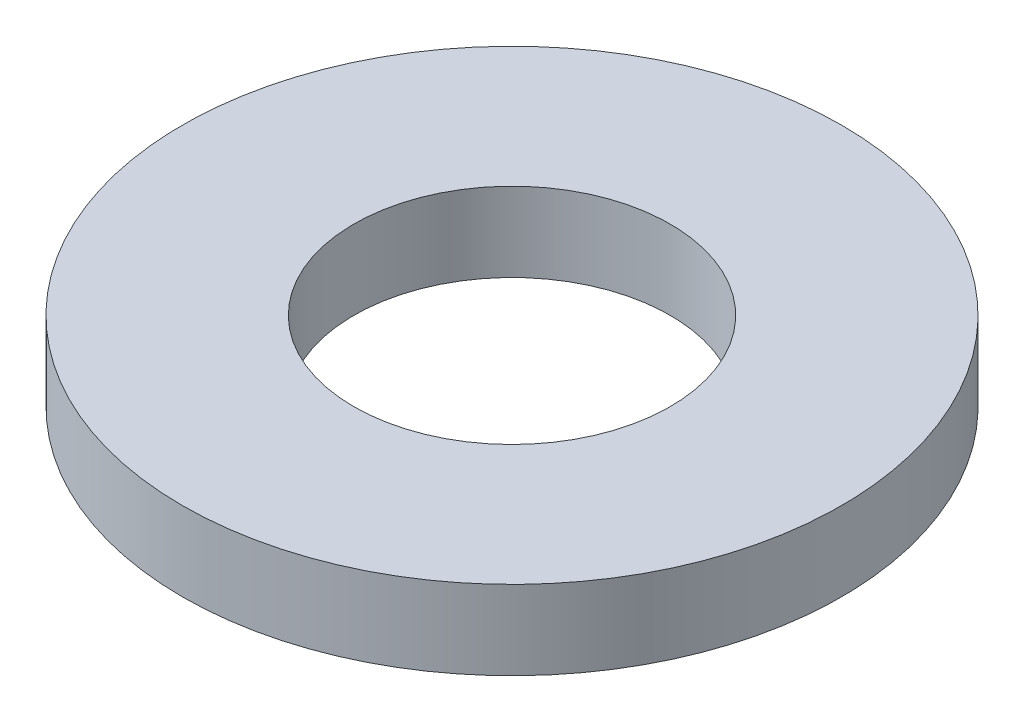
SolidWorks part; units mm, degrees
material "Plain Carbon Steel"
ref_plane "Front Plane" through (0, 0, 0) normal (0, 0, 1) x (1, 0, 0)
ref_plane "Top Plane" through (0, 0, 0) normal (0, 1, 0) x (1, 0, 0)
ref_plane "Right Plane" through (0, 0, 0) normal (1, 0, 0) x (0, 0, -1)
sketch "Sketch1" plane through (0, 0, 0) normal (0, 1, 0) x (1, 0, 0)
  circle A0 centre (0, 0) radius 12.5
  circle A1 centre (0, 0) radius 6
  dimension "D1" = 25
  dimension "D2" = 12
extrude "Boss-Extrude1" add sketch "Sketch1" along normal mid plane 3
